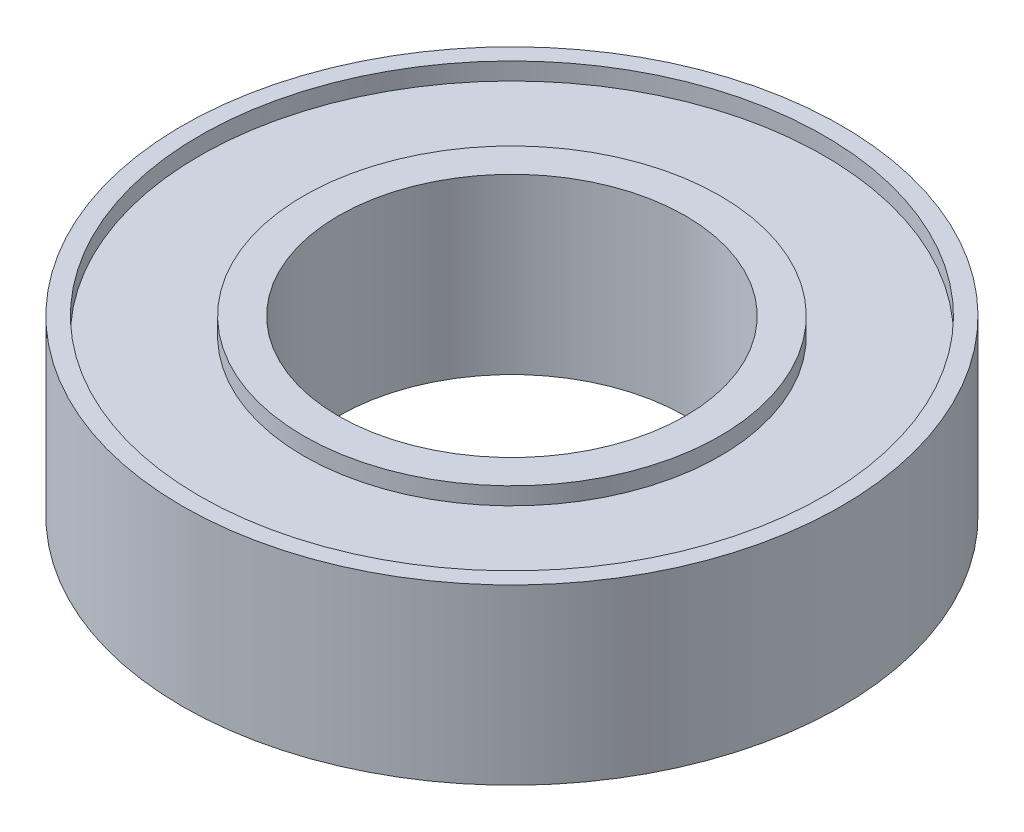
SolidWorks part; units mm, degrees
ref_plane "Front Plane" through (0, 0, 0) normal (0, 0, 1) x (1, 0, 0)
ref_plane "Top Plane" through (0, 0, 0) normal (0, 1, 0) x (1, 0, 0)
ref_plane "Right Plane" through (0, 0, 0) normal (1, 0, 0) x (0, 0, -1)
sketch "Sketch1" plane through (0, 0, 0) normal (0, 1, 0) x (1, 0, 0)
  circle A0 centre (0, 0) radius 9.5
  circle A1 centre (0, 0) radius 5
extrude "Boss-Extrude1" add sketch "Sketch1" along normal blind 5
sketch "Sketch2" plane through (0, 5, 0) normal (0, 1, 0) x (1, 0, 0)
  circle A0 centre (0, 0) radius 9
  circle A1 centre (0, 0) radius 6
extrude "Cut-Extrude1" cut sketch "Sketch2" against normal blind 0.5
sketch "Sketch3" plane through (0, 0, 0) normal (0, -1, 0) x (1, 0, 0)
  circle A0 centre (0, 0) radius 9
  circle A1 centre (0, 0) radius 6
extrude "Cut-Extrude2" cut sketch "Sketch3" against normal blind 0.5
